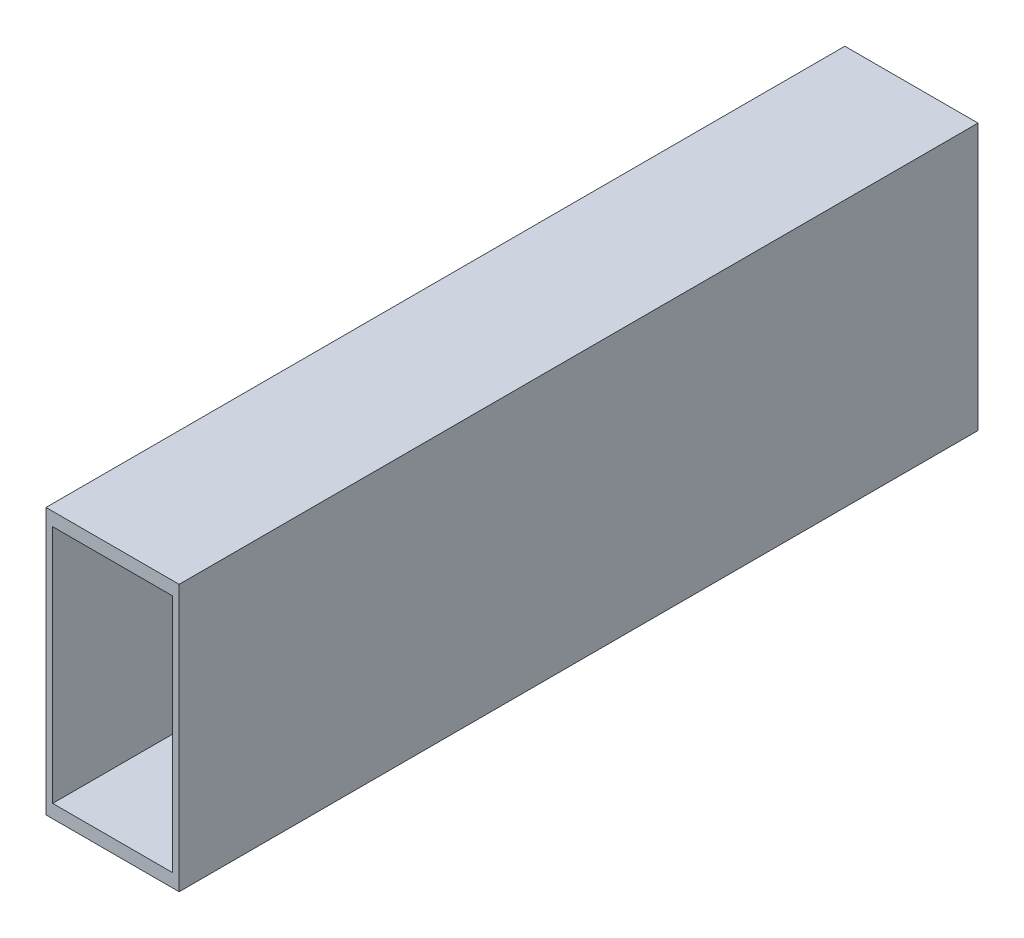
SolidWorks part; units mm, degrees
ref_plane "Front Plane" through (0, 0, 0) normal (0, 0, 1) x (1, 0, 0)
ref_plane "Top Plane" through (0, 0, 0) normal (0, 1, 0) x (1, 0, 0)
ref_plane "Right Plane" through (0, 0, 0) normal (1, 0, 0) x (0, 0, -1)
sketch "Sketch1" plane through (0, 0, 0) normal (0, 0, 1) x (1, 0, 0)
  line L1 (-250, -500) -> (250, -500)
  line L2 (-250, -500) -> (-250, 500)
  line L3 (-250, 500) -> (250, 500)
  line L4 (250, -500) -> (250, 500)
  line L5 (-250, -500) -> (250, 500) construction
  line L6 (-250, 500) -> (250, -500) construction
  line L7 (-225, -450) -> (225, -450)
  line L8 (-225, -450) -> (-225, 450)
  line L9 (-225, 450) -> (225, 450)
  line L10 (225, -450) -> (225, 450)
  line L11 (-225, -450) -> (225, 450) construction
  line L12 (-225, 450) -> (225, -450) construction
  point P0 (0, 0)
  point P5 (0, 0)
  dimension "D1" = 1000
  dimension "D2" = 500
  dimension "D3" = 900
  dimension "D4" = 450
extrude "Boss-Extrude1" add sketch "Sketch1" along normal mid plane 3000
